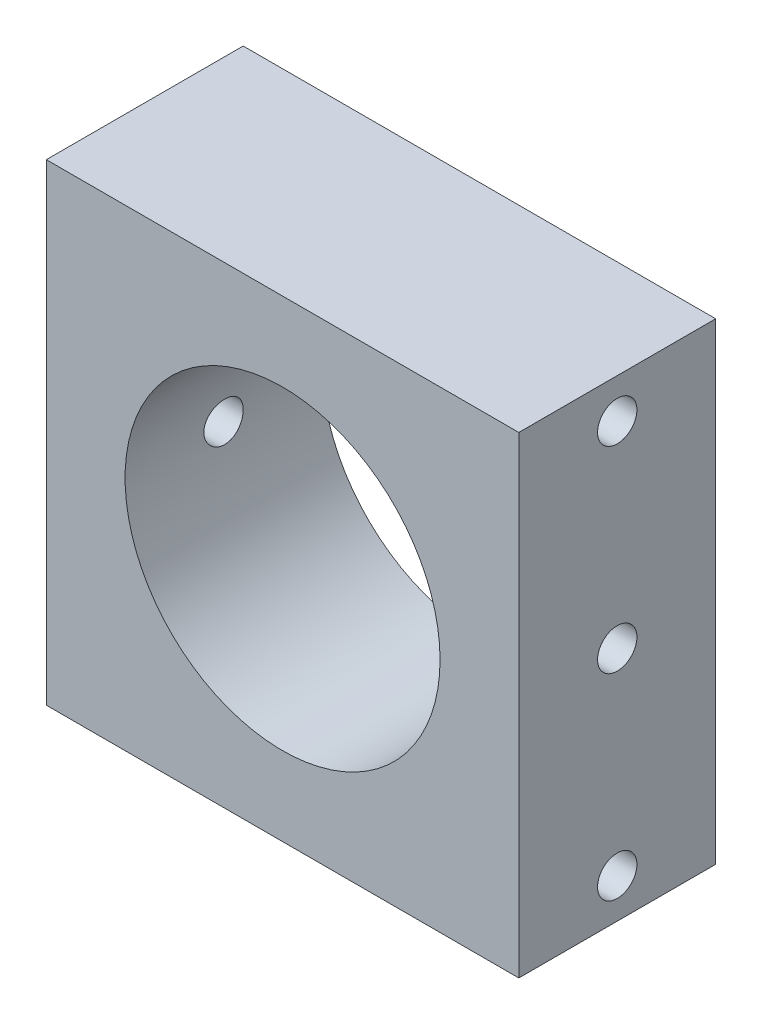
SolidWorks part; units mm, degrees
ref_plane "Front Plane" through (0, 0, 0) normal (0, 0, 1) x (1, 0, 0)
ref_plane "Top Plane" through (0, 0, 0) normal (0, 1, 0) x (1, 0, 0)
ref_plane "Right Plane" through (0, 0, 0) normal (1, 0, 0) x (0, 0, -1)
sketch "Sketch1" plane through (0, 0, 0) normal (0, 0, 1) x (1, 0, 0)
  line L0 (0, 0) -> (0, 191362.0965) construction
  line L1 (0, 0) -> (191362.0965, 0) construction
  line L2 (-20, 0) -> (-30, 0)
  line L3 (-30, -30) -> (-30, 30)
  line L4 (-30, 30) -> (30, 30)
  line L5 (20, 0) -> (30, 0)
  line L6 (30, -30) -> (30, 30)
  line L7 (-30, -30) -> (30, -30)
  circle A0 centre (0, 0) radius 20
  point P13 (0, 30)
  dimension "D1" = 20
  dimension "D2" = 60
  dimension "D3" = 30
extrude "Boss-Extrude1" add sketch "Sketch1" along normal blind 25 contours A0 L5 L6 L4 L3 L2 | A0 L2 L3 L7 L6 L5
sketch "Sketch2" plane through (30, 0, 0) normal (1, 0, 0) x (0, 0, -1)
  line L0 (-12.5, 30) -> (-12.5, -30) construction
  line L1 (-25, 30) -> (0, 30) construction
  line L3 (-25, 30) -> (0, 30) construction
  line L4 (-25, -30) -> (0, -30) construction
  line L5 (0, 0) -> (-25, 0) construction
  line L6 (-25, -30) -> (-25, 30) construction
  circle A0 centre (-12.5, 25) radius 2.5
  circle A1 centre (-12.5, -25) radius 2.5
  circle A2 centre (-12.5, 0) radius 2.5
  dimension "D1" = 5
  dimension "D4" = 5
  dimension "D2" = 5
  dimension "D3" = 5
extrude "Cut-Extrude1" cut sketch "Sketch2" against normal through all
fillet "Fillet1" [suppressed] radius 20
